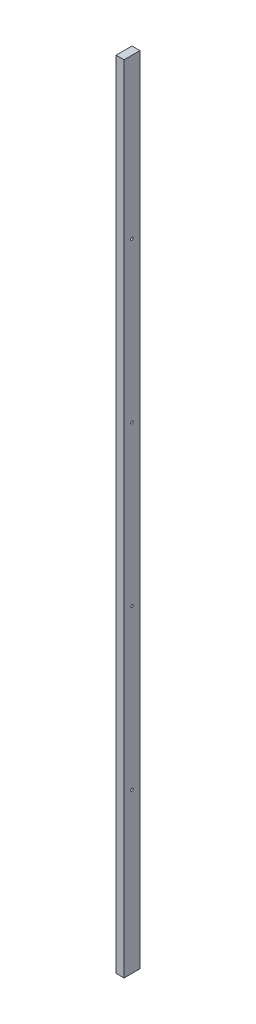
SolidWorks part; units mm, degrees
ref_plane "Спереди" through (0, 0, 0) normal (0, 0, 1) x (1, 0, 0)
ref_plane "Сверху" through (0, 0, 0) normal (0, 1, 0) x (1, 0, 0)
ref_plane "Справа" through (0, 0, 0) normal (1, 0, 0) x (0, 0, -1)
other "Configuration Table"
sketch "Эскиз1" plane through (0, 0, 0) normal (0, 1, 0) x (1, 0, 0)
  line L1 (12.5, 25) -> (-12.5, 25)
  line L2 (12.5, 25) -> (12.5, -25)
  line L3 (12.5, -25) -> (-12.5, -25)
  line L4 (-12.5, 25) -> (-12.5, -25)
  line L5 (12.5, 25) -> (-12.5, -25) construction
  line L6 (12.5, -25) -> (-12.5, 25) construction
  point P0 (0, 0)
extrude "Бобышка-Вытянуть1" add sketch "Эскиз1" along normal blind 2500
sketch "Эскиз2" plane through (12.5, 0, 0) normal (1, 0, 0) x (0, 0, -1)
  line L0 (0, 0) -> (0, 500) construction
  line L1 (0, 500) -> (0, 1000) construction
  line L2 (0, 1000) -> (0, 1500) construction
  line L3 (0, 1500) -> (0, 2000) construction
  line L4 (0, 2000) -> (0, 2500) construction
  line L5 (-25, 2500) -> (25, 2500) construction
  circle A0 centre (0, 500) radius 4
  circle A1 centre (0, 1000) radius 4
  circle A2 centre (0, 1500) radius 4
  circle A3 centre (0, 2000) radius 4
extrude "Вырез-Вытянуть1" cut sketch "Эскиз2" against normal blind 100
